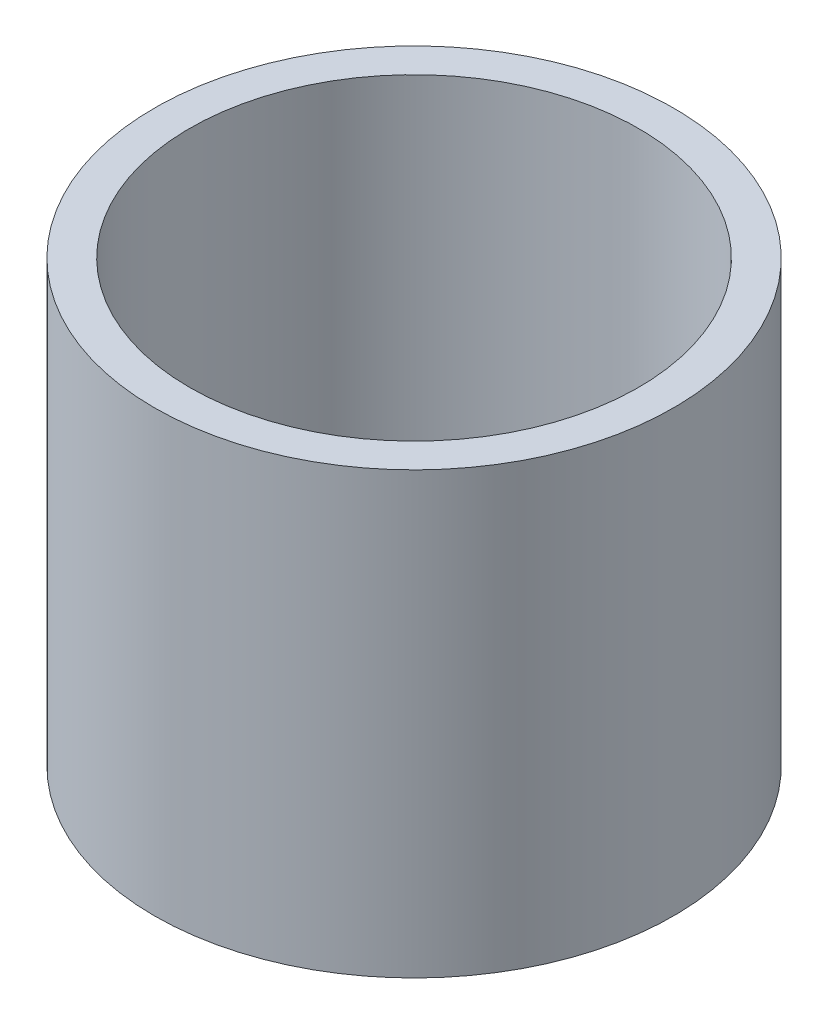
SolidWorks part; units mm, degrees
ref_plane "Front Plane" through (0, 0, 0) normal (0, 0, 1) x (1, 0, 0)
ref_plane "Top Plane" through (0, 0, 0) normal (0, 1, 0) x (1, 0, 0)
ref_plane "Right Plane" through (0, 0, 0) normal (1, 0, 0) x (0, 0, -1)
sketch "Sketch1" plane through (0, 0, 0) normal (0, 1, 0) x (1, 0, 0)
  circle A0 centre (0, 0) radius 5.1
  circle A1 centre (0, 0) radius 5.9
  dimension "D1" = 10.2
  dimension "D2" = 11.8
extrude "Boss-Extrude1" add sketch "Sketch1" along normal blind 10
